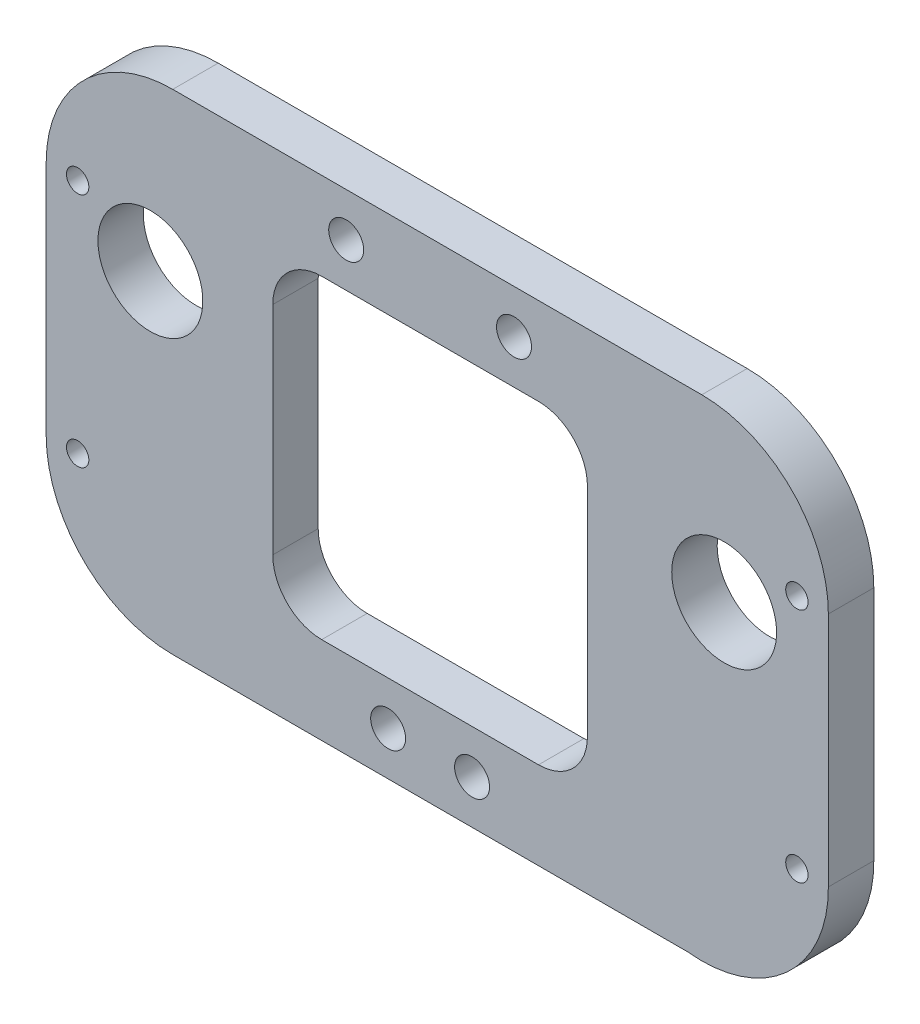
SolidWorks part; units mm, degrees
ref_plane "前视基准面" through (0, 0, 0) normal (0, 0, 1) x (1, 0, 0)
ref_plane "上视基准面" through (0, 0, 0) normal (0, 1, 0) x (1, 0, 0)
ref_plane "右视基准面" through (0, 0, 0) normal (1, 0, 0) x (0, 0, -1)
sketch "草图1" plane through (0, 0, 0) normal (0, 0, 1) x (1, 0, 0)
  line L0 (-36.8001, 35) -> (38.8503, 35)
  line L5 (56.9503, 16.9) -> (56.9503, -16.9)
  line L6 (-54.9, 16.9) -> (-54.9, -16.9)
  line L7 (-36.8001, -35) -> (36.8001, -35)
  line L8 (-15.5, 22.5) -> (15.5, 22.5)
  line L9 (22.5, 15.5) -> (22.5, -15.5)
  line L14 (15.5, -22.5) -> (-15.5, -22.5)
  line L15 (-22.5, 15.5) -> (-22.5, -15.5)
  arc A0 (-36.8001, 35) -> (-54.9, 16.9) centre (-36.8001, 16.9) ccw
  arc A1 (38.8503, 35) -> (56.9503, 16.9) centre (38.8503, 16.9) cw
  arc A2 (36.8001, -35) -> (56.9503, -16.9) centre (38.8507, -17.0166) ccw
  arc A3 (-36.8001, -35) -> (-54.9, -16.9) centre (-36.8001, -16.9) cw
  circle A4 centre (-50.4, 16.9) radius 1.6
  circle A5 centre (-40, 10.9) radius 7.5
  circle A6 centre (52.4503, 16.9) radius 1.6
  circle A7 centre (42.0503, 10.9) radius 7.5
  circle A8 centre (52.4503, -16.9) radius 1.6
  circle A9 centre (-50.4, -16.9) radius 1.6
  arc A10 (-15.5, 22.5) -> (-22.5, 15.5) centre (-15.5, 15.5) ccw
  arc A11 (15.5, 22.5) -> (22.5, 15.5) centre (15.5, 15.5) cw
  arc A12 (15.5, -22.5) -> (22.5, -15.5) centre (15.5, -15.5) ccw
  arc A13 (-15.5, -22.5) -> (-22.5, -15.5) centre (-15.5, -15.5) cw
  point P2 (0, 0)
extrude "凸台-拉伸1" add sketch "草图1" along normal blind 6.5
sketch "草图3" plane through (0, 0, 6.5) normal (0, 0, 1) x (1, 0, 0)
  circle A0 centre (-12, 28.75) radius 2.5
  circle A1 centre (12, 28.75) radius 2.5
  circle A2 centre (-6, -28.75) radius 2.5
  circle A3 centre (6, -28.75) radius 2.5
extrude "切除-拉伸1" cut sketch "草图3" against normal through all
